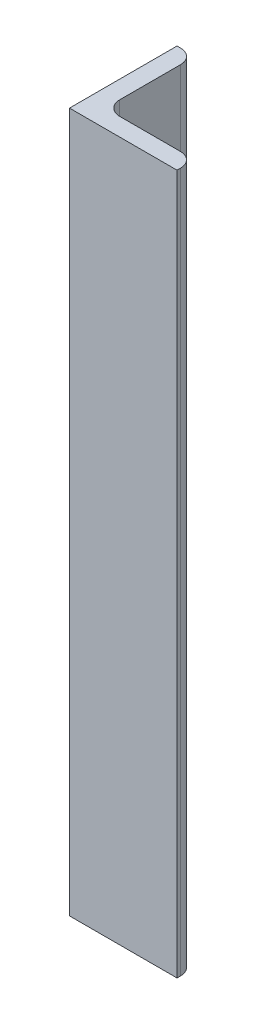
SolidWorks part; units mm, degrees
ref_plane "Front Plane" through (0, 0, 0) normal (0, 0, 1) x (1, 0, 0)
ref_plane "Top Plane" through (0, 0, 0) normal (0, 1, 0) x (1, 0, 0)
ref_plane "Right Plane" through (0, 0, 0) normal (1, 0, 0) x (0, 0, -1)
sketch "Sketch1" plane through (0, 0, 0) normal (0, 1, 0) x (1, 0, 0)
  line L0 (0, 0) -> (0, 19.05)
  line L1 (0, 19.05) -> (3.175, 19.05)
  line L2 (3.175, 19.05) -> (3.175, 3.175)
  line L3 (3.175, 3.175) -> (19.05, 3.175)
  line L4 (19.05, 3.175) -> (19.05, 0)
  line L5 (19.05, 0) -> (0, 0)
  dimension "D1" = 19.05
  dimension "D2" = 3.175
extrude "Boss-Extrude1" add sketch "Sketch1" along normal blind 123.952
fillet "Fillet1" radius 2.54 3 edges at (19.05, 61.976, -3.175) (3.175, 61.976, -19.05) (3.175, 61.976, -3.175)
